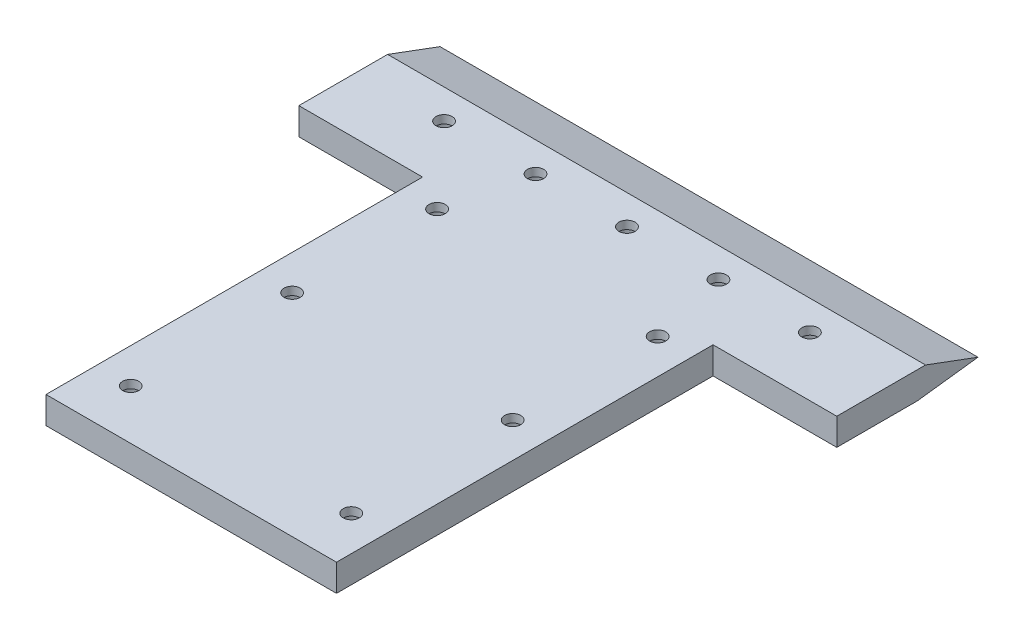
SolidWorks part; units mm, degrees
ref_plane "Alzado" through (0, 0, 0) normal (0, 0, 1) x (1, 0, 0)
ref_plane "Planta" through (0, 0, 0) normal (0, 1, 0) x (1, 0, 0)
ref_plane "Vista lateral" through (0, 0, 0) normal (1, 0, 0) x (0, 0, -1)
sketch "Croquis1" plane through (0, 0, 0) normal (0, 1, 0) x (1, 0, 0)
  line L16 (-46.1165, 70) -> (-46.1165, 100)
  line L17 (-46.1165, 100) -> (53.8835, 100)
  line L18 (53.8835, 100) -> (53.8835, 70)
  line L22 (-46.1165, 93) -> (53.8835, 93)
  line L29 (30.8835, 40) -> (30.8835, 70)
  line L30 (30.8835, 70) -> (53.8835, 70)
  line L33 (-23.1165, 40) -> (-23.1165, 70)
  line L34 (-23.1165, 70) -> (-46.1165, 70)
  line L35 (-19.1165, 0) -> (26.8835, 0)
  line L36 (3.8835, 0) -> (3.8835, 100) construction
  line L37 (-23.1165, 40) -> (-23.1165, 0)
  line L38 (-23.1165, 0) -> (-19.1165, 0)
  line L39 (30.8835, 40) -> (30.8835, 0)
  line L40 (30.8835, 0) -> (26.8835, 0)
  circle A1 centre (24.3835, 9.25) radius 1.5
  circle A2 centre (24.3835, 39.25) radius 1.5
  circle A3 centre (24.3835, 66.2) radius 1.5
  circle A4 centre (3.8835, 87.7) radius 1.5
  circle A5 centre (20.8835, 87.7) radius 1.5
  circle A6 centre (37.8835, 87.7) radius 1.5
  circle A7 centre (-30.1165, 87.7) radius 1.5
  circle A8 centre (-13.1165, 87.7) radius 1.5
  circle A9 centre (-16.6165, 66.2) radius 1.5
  circle A10 centre (-16.6165, 39.25) radius 1.5
  circle A11 centre (-16.6165, 9.25) radius 1.5
  dimension "D11" = 3
  dimension "D13" = 3
  dimension "D18" = 3
  dimension "D20" = 3
  dimension "D22" = 3
  dimension "D23" = 3
  dimension "D2" = 27
  dimension "D3" = 100
  dimension "D4" = 29.5
  dimension "D5" = 30
  dimension "D6" = 23
  dimension "D7" = 27
  dimension "D8" = 23
  dimension "D14" = 100
  dimension "D15" = 30
  dimension "D16" = 66.2
  dimension "D17" = 29.5
  dimension "D19" = 7
  dimension "D21" = 21.5
  dimension "D24" = 17
  dimension "D25" = 17
extrude "Saliente-Extruir1" add sketch "Croquis1" along normal blind 5.02 contours L29 L30 L18 L17 L16 L34 L33 L37 L38 L35 L40 L39
ref_plane "Plano1" through (-46.1165, 0, 0) normal (-1, 0, 0) x (0, 0, 1)
sketch "Croquis2" plane through (-46.1165, 0, 0) normal (-1, 0, 0) x (0, 0, 1)
  line L0 (-100, 0) -> (-86.5, 5.02)
  line L1 (-70, 5.02) -> (-100, 5.02) construction
  line L2 (-86.5, 5.02) -> (-100, 5.02)
  line L3 (-100, 5.02) -> (-100, 0)
  line L4 (-97.4997, 0) -> (-100, 0) construction
  line L5 (-70, 0) -> (-100, 0) construction
  line L6 (-100, 0) -> (-82.4932, 5.02) construction
  line L7 (-70, 5.02) -> (-100, 5.02) construction
  dimension "D1" = 13.5
extrude "Cortar-Extruir1" cut sketch "Croquis2" against normal blind 100
sketch "Croquis4" plane through (0, 0, 0) normal (0, -1, 0) x (1, 0, 0)
  line L0 (-46.1165, -93) -> (53.8835, -93) construction
  line L1 (-46.1165, -93) -> (53.8835, -93)
  line L2 (-0.6919, -81) -> (3.8835, -81) construction
  line L3 (3.8835, -81) -> (20.8835, -81) construction
  line L4 (-46.1165, -93) -> (53.8835, -93)
  line L5 (-46.1165, -93) -> (53.8835, -93)
  line L6 (20.8835, -81) -> (43.2842, -81) construction
  line L7 (3.8835, -100) -> (3.8835, -64.1057) construction
  line L12 (-46.1165, -70) -> (-46.1165, -100)
  line L13 (-46.1165, -100) -> (53.8835, -100)
  line L14 (53.8835, -100) -> (53.8835, -70)
  line L15 (53.8835, -70) -> (30.8835, -70)
  line L16 (30.8835, -70) -> (30.8835, -40)
  line L17 (30.8835, -40) -> (30.8835, 0)
  line L18 (30.8835, -40) -> (30.8835, 0)
  line L19 (26.8835, 0) -> (-19.1165, 0)
  line L20 (30.8835, 0) -> (26.8835, 0)
  line L21 (30.8835, 0) -> (26.8835, 0)
  line L22 (-23.1165, -40) -> (-23.1165, -70)
  line L23 (-23.1165, -70) -> (-46.1165, -70)
  line L24 (-46.1165, -70) -> (-46.1165, -100)
  line L25 (-46.1165, -100) -> (53.8835, -100)
  line L26 (53.8835, -100) -> (53.8835, -70)
  line L27 (53.8835, -70) -> (30.8835, -70)
  line L28 (30.8835, -70) -> (30.8835, -40)
  line L31 (26.8835, 0) -> (-19.1165, 0)
  line L34 (-23.1165, -40) -> (-23.1165, -70)
  line L35 (-23.1165, -70) -> (-46.1165, -70)
  line L44 (-19.1165, 0) -> (-23.1165, 0)
  line L45 (-19.1165, 0) -> (-23.1165, 0)
  line L46 (-23.1165, 0) -> (-23.1165, -40)
  line L47 (-23.1165, 0) -> (-23.1165, -40)
  circle A0 centre (3.8835, -81) radius 1.5
  circle A1 centre (24.3835, -9.25) radius 1.5
  circle A2 centre (24.3835, -9.25) radius 1.5
  circle A5 centre (-30.1165, -81) radius 1.5
  circle A7 centre (-13.1165, -81) radius 1.5
  circle A11 centre (24.3835, -66.2) radius 1.5
  circle A12 centre (24.3835, -66.2) radius 1.5
  circle A13 centre (24.3835, -39.25) radius 1.5
  circle A14 centre (24.3835, -39.25) radius 1.5
  circle A15 centre (-16.6165, -9.25) radius 1.5
  circle A16 centre (-16.6165, -9.25) radius 1.5
  circle A17 centre (-16.6165, -39.25) radius 1.5
  circle A18 centre (-16.6165, -39.25) radius 1.5
  circle A19 centre (-16.6165, -66.2) radius 1.5
  circle A20 centre (-16.6165, -66.2) radius 1.5
  circle A25 centre (20.8835, -81) radius 1.5
  circle A26 centre (37.8835, -81) radius 1.5
  point P10 (3.8835, -100)
  dimension "D14" = 3
  dimension "D15" = 3
  dimension "D16" = 3
  dimension "D3" = 19
  dimension "D4" = 17
  dimension "D5" = 17
  dimension "D1" = 0
  dimension "D6" = 0
  dimension "D7" = 0
  dimension "D8" = 0
  dimension "D9" = 0
  dimension "D10" = 0
  dimension "D11" = 0
extrude "Cortar-Extruir2" cut sketch "Croquis4" against normal blind 10
sketch "Croquis5" plane through (0, 0, 0) normal (0, -1, 0) x (1, 0, 0)
  line L0 (3.8835, 0) -> (3.8835, -112.0323) construction
  line L1 (-23.1165, 0) -> (30.8835, 0) construction
  circle A1 centre (24.3835, -9.25) radius 3
  circle A2 centre (24.3835, -39.25) radius 3
  circle A3 centre (24.3835, -66.2) radius 3
  circle A9 centre (-16.6165, -66.2) radius 3
  circle A10 centre (-16.6165, -39.25) radius 3
  circle A11 centre (-16.6165, -9.25) radius 3
  circle A12 centre (3.8835, -81) radius 3
  circle A13 centre (20.8835, -81) radius 3
  circle A14 centre (37.8835, -81) radius 3
  circle A15 centre (-30.1165, -81) radius 3
  circle A16 centre (-13.1165, -81) radius 3
  dimension "D2" = 6
  dimension "D3" = 6
  dimension "D4" = 6
  dimension "D8" = 6
  dimension "D9" = 6
  dimension "D10" = 6
extrude "Cortar-Extruir3" cut sketch "Croquis5" against normal blind 3.5
sketch "Croquis6" plane through (-46.1165, 0, 0) normal (-1, 0, 0) x (0, 0, 1)
  line L0 (-100, 0) -> (-85, 0)
  line L1 (-70, 0) -> (-100, 0) construction
  line L2 (-85, 0) -> (-96.2508, 1.3941)
  line L3 (-100, 0) -> (-86.5, 5.02) construction
  line L4 (-96.2508, 1.3941) -> (-100, 0)
  dimension "D1" = 4
  dimension "D2" = 15
extrude "Cortar-Extruir4" cut sketch "Croquis6" against normal blind 100
